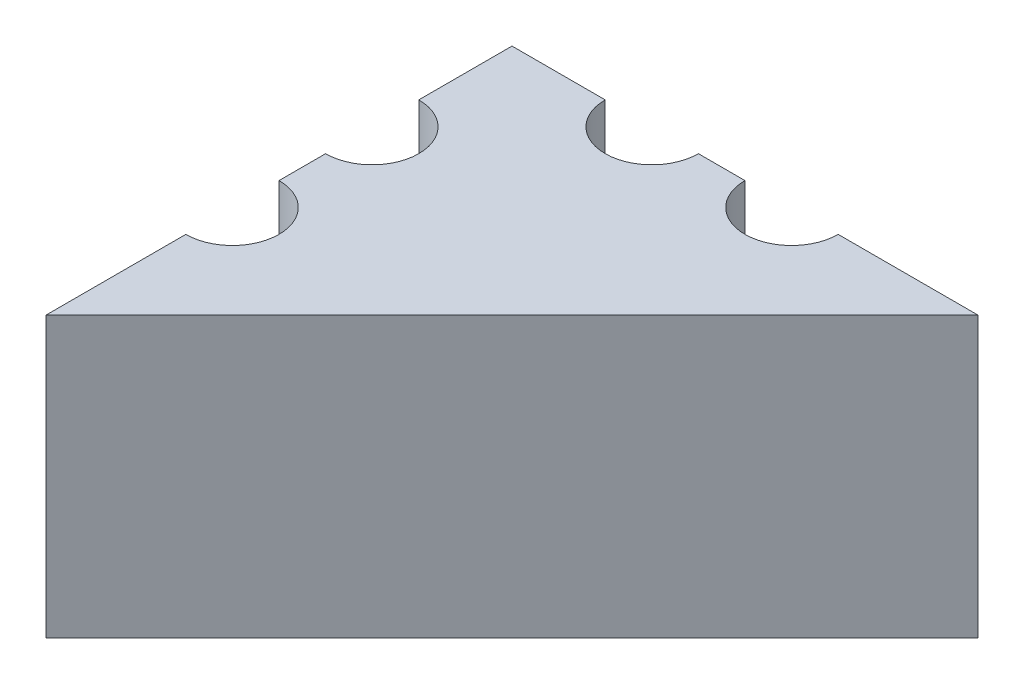
SolidWorks part; units mm, degrees
ref_plane "Front Plane" through (0, 0, 0) normal (0, 0, 1) x (1, 0, 0)
ref_plane "Top Plane" through (0, 0, 0) normal (0, 1, 0) x (1, 0, 0)
ref_plane "Right Plane" through (0, 0, 0) normal (1, 0, 0) x (0, 0, -1)
sketch "Sketch1" plane through (0, 0, 0) normal (0, 1, 0) x (1, 0, 0)
  line L0 (0, 0) -> (10, 0)
  line L1 (10, 0) -> (0, -10)
  line L2 (0, -10) -> (0, 0)
  dimension "D1" = 10
  dimension "D2" = 10
extrude "Boss-Extrude1" add sketch "Sketch1" along normal blind 6
sketch "Sketch2" plane through (0, 6, 0) normal (0, 1, 0) x (1, 0, 0)
  line L0 (0, 0) -> (0, -10) construction
  line L1 (10, 0) -> (0, 0) construction
  circle A0 centre (0, -6) radius 1
  circle A1 centre (0, -3) radius 1
  circle A2 centre (3, 0) radius 1
  circle A3 centre (6, 0) radius 1
  dimension "D1" = 2
  dimension "D2" = 3
  dimension "D3" = 3
  dimension "D4" = 3
  dimension "D5" = 3
extrude "Cut-Extrude1" cut sketch "Sketch2" against normal through all
